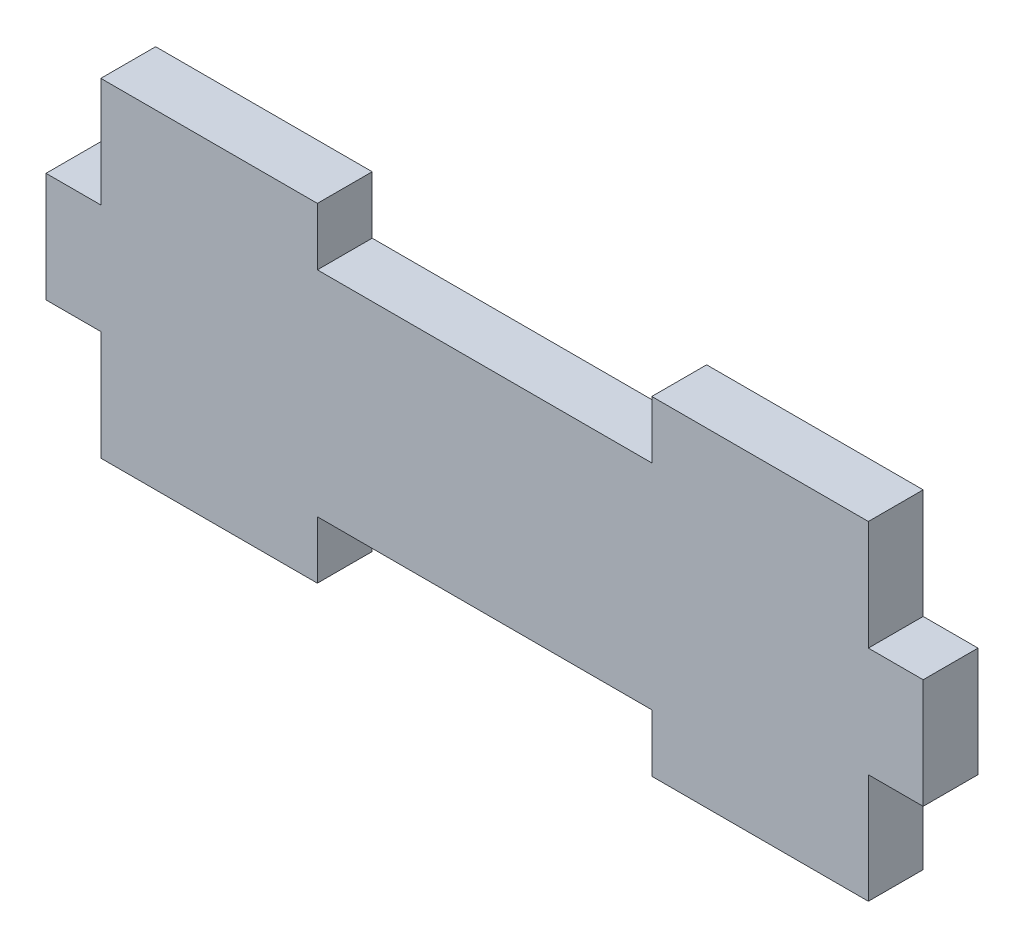
SolidWorks part; units mm, degrees
ref_plane "Front Plane" through (0, 0, 0) normal (0, 0, 1) x (1, 0, 0)
ref_plane "Top Plane" through (0, 0, 0) normal (0, 1, 0) x (1, 0, 0)
ref_plane "Right Plane" through (0, 0, 0) normal (1, 0, 0) x (0, 0, -1)
sketch "Model" plane through (0, 0, 0) normal (0, 0, 1) x (1, 0, 0)
  line L0 (-181.253, -123.7291) -> (-181.253, -133.7291)
  line L1 (-181.253, -133.7291) -> (-186.253, -133.7291)
  line L2 (-161.503, -148.4791) -> (-131.003, -148.4791)
  line L3 (-106.253, -143.7291) -> (-111.253, -143.7291)
  line L4 (-186.253, -143.7291) -> (-181.253, -143.7291)
  line L5 (-181.253, -153.7291) -> (-161.503, -153.7291)
  line L6 (-181.253, -143.7291) -> (-181.253, -153.7291)
  line L7 (-161.503, -123.7291) -> (-181.253, -123.7291)
  line L8 (-186.253, -133.7291) -> (-186.253, -143.7291)
  line L9 (-161.503, -153.7291) -> (-161.503, -148.4791)
  line L10 (-131.003, -148.4791) -> (-131.003, -153.7291)
  line L11 (-111.253, -153.7291) -> (-131.003, -153.7291)
  line L12 (-111.253, -143.7291) -> (-111.253, -153.7291)
  line L13 (-106.253, -133.7291) -> (-106.253, -143.7291)
  line L14 (-111.253, -133.7291) -> (-106.253, -133.7291)
  line L15 (-111.253, -123.7291) -> (-111.253, -133.7291)
  line L16 (-131.003, -123.7291) -> (-111.253, -123.7291)
  line L17 (-131.003, -128.9791) -> (-131.003, -123.7291)
  line L18 (-161.503, -128.9791) -> (-131.003, -128.9791)
  line L19 (-161.503, -123.7291) -> (-161.503, -128.9791)
  line L20 (-154.4137, -142.4791) -> (-138.0923, -142.4791)
  line L21 (-126.8852, -146.7291) -> (-126.8852, -151.7291)
  line L22 (-127.8852, -149.7291) -> (-126.8852, -151.7291)
  line L23 (-125.8852, -149.7291) -> (-126.8852, -151.7291)
  line L24 (-121.1374, -150.5624) -> (-121.1374, -150.2564)
  line L25 (-121.1577, -150.6587) -> (-121.1374, -150.5624)
  line L26 (-116.2735, -151.0431) -> (-116.7144, -151.008)
  line L27 (-123.3653, -147.1199) -> (-123.3852, -147.2159)
  line L28 (-117.3773, -150.6585) -> (-117.317, -150.7473)
  line L29 (-119.3329, -146.7291) -> (-119.9448, -149.2204)
  line L30 (-121.2185, -150.7481) -> (-121.1577, -150.6587)
  line L31 (-121.4621, -150.9058) -> (-121.2185, -150.7481)
  line L32 (-122.6999, -146.7711) -> (-123.0667, -146.8788)
  line L33 (-117.3974, -146.7352) -> (-117.3974, -148.8517)
  line L34 (-117.3974, -148.8517) -> (-117.1788, -148.5973)
  line L35 (-117.3773, -150.6585) -> (-117.3974, -150.5624)
  line L36 (-119.9448, -149.2204) -> (-118.6835, -149.2261)
  line L37 (-122.7061, -151.0088) -> (-122.2613, -151.0431)
  line L38 (-117.3974, -146.7352) -> (-115.2245, -146.7352)
  line L39 (-117.1788, -148.5973) -> (-116.9478, -148.4708)
  line L40 (-116.9478, -148.4708) -> (-116.2735, -148.3709)
  line L41 (-121.1374, -147.2159) -> (-121.1577, -147.1223)
  line L42 (-123.3852, -147.2159) -> (-123.3852, -150.5624)
  line L43 (-123.3056, -150.7512) -> (-123.0667, -150.9058)
  line L44 (-122.2613, -151.0431) -> (-121.8179, -151.0088)
  line L45 (-118.209, -151.0431) -> (-118.6835, -149.2261)
  line L46 (-118.6835, -149.2261) -> (-119.3329, -146.7291)
  line L47 (-116.7144, -151.008) -> (-117.0758, -150.9026)
  line L48 (-123.0667, -150.9058) -> (-122.7061, -151.0088)
  line L49 (-123.3056, -147.0317) -> (-123.3653, -147.1199)
  line L50 (-121.4621, -146.8788) -> (-121.8273, -146.7711)
  line L51 (-121.8273, -146.7711) -> (-122.2613, -146.7352)
  line L52 (-123.0667, -146.8788) -> (-123.3056, -147.0317)
  line L53 (-123.3653, -150.6611) -> (-123.3056, -150.7512)
  line L54 (-117.317, -150.7473) -> (-117.0758, -150.9026)
  line L55 (-121.1374, -147.2159) -> (-121.1374, -147.5219)
  line L56 (-122.2613, -146.7352) -> (-122.6999, -146.7711)
  line L57 (-123.3852, -150.5624) -> (-123.3653, -150.6611)
  line L58 (-121.1577, -147.1223) -> (-121.2185, -147.0349)
  line L59 (-121.8179, -151.0088) -> (-121.4621, -150.9058)
  line L60 (-121.2185, -147.0349) -> (-121.4621, -146.8788)
  line L61 (-115.1697, -150.6585) -> (-115.2299, -150.7473)
  line L62 (-115.2299, -150.7473) -> (-115.4711, -150.9026)
  line L63 (-115.4711, -148.5114) -> (-115.2299, -148.6667)
  line L64 (-115.4711, -150.9026) -> (-115.8325, -151.008)
  line L65 (-115.8325, -148.406) -> (-115.4711, -148.5114)
  line L66 (-116.2735, -148.3709) -> (-115.8325, -148.406)
  line L67 (-119.9448, -149.2204) -> (-120.3943, -151.0431)
  line L68 (-115.2299, -148.6667) -> (-115.1697, -148.7555)
  line L69 (-115.1496, -150.5624) -> (-115.1697, -150.6585)
  line L70 (-115.8325, -151.008) -> (-116.2735, -151.0431)
  line L71 (-115.1697, -148.7555) -> (-115.1496, -148.8517)
  line L72 (-115.1496, -148.8517) -> (-115.1496, -150.5624)
  line L73 (-115.4904, -130.5886) -> (-115.8517, -130.694)
  line L74 (-115.8517, -130.694) -> (-116.2927, -130.7291)
  line L75 (-120.4136, -128.5502) -> (-120.4136, -126.4212)
  line L76 (-121.1566, -127.2078) -> (-121.1566, -126.9019)
  line L77 (-117.3362, -130.4333) -> (-117.3965, -130.3445)
  line L78 (-117.0951, -130.5886) -> (-117.3362, -130.4333)
  line L79 (-120.4136, -130.7291) -> (-120.4136, -128.5502)
  line L80 (-118.5841, -128.5502) -> (-120.4136, -128.5502)
  line L81 (-118.2844, -126.4212) -> (-120.4136, -126.4212)
  line L82 (-117.4166, -130.2483) -> (-117.3965, -130.3445)
  line L83 (-121.1769, -126.8083) -> (-121.1566, -126.9019)
  line L84 (-115.1688, -130.2483) -> (-115.1889, -130.3445)
  line L85 (-115.1889, -130.3445) -> (-115.2492, -130.4333)
  line L86 (-115.2492, -130.4333) -> (-115.4904, -130.5886)
  line L87 (-115.2492, -128.3527) -> (-115.1889, -128.4415)
  line L88 (-115.1889, -128.4415) -> (-115.1688, -128.5377)
  line L89 (-115.1688, -128.5377) -> (-115.1688, -130.2483)
  line L90 (-116.9671, -128.1568) -> (-117.1981, -128.2832)
  line L91 (-116.2927, -128.0569) -> (-115.8517, -128.092)
  line L92 (-115.8517, -128.092) -> (-115.4904, -128.1974)
  line L93 (-115.4904, -128.1974) -> (-115.2492, -128.3527)
  line L94 (-115.2438, -126.4212) -> (-117.4166, -126.4212)
  line L95 (-117.4166, -126.4212) -> (-117.4166, -128.5377)
  line L96 (-117.4166, -128.5377) -> (-117.1981, -128.2832)
  line L97 (-116.2927, -128.0569) -> (-116.9671, -128.1568)
  line L98 (-116.2927, -130.7291) -> (-116.7337, -130.694)
  line L99 (-116.7337, -130.694) -> (-117.0951, -130.5886)
  line L100 (-121.1769, -130.3447) -> (-121.2378, -130.4341)
  line L101 (-123.086, -130.5917) -> (-123.3248, -130.4372)
  line L102 (-123.3845, -130.3471) -> (-123.4044, -130.2483)
  line L103 (-123.4044, -130.2483) -> (-123.4044, -126.9019)
  line L104 (-121.1566, -129.9424) -> (-121.1566, -130.2483)
  line L105 (-121.8372, -130.6948) -> (-122.2805, -130.7291)
  line L106 (-122.2805, -130.7291) -> (-122.7254, -130.6948)
  line L107 (-123.4044, -126.9019) -> (-123.3845, -126.8059)
  line L108 (-123.3845, -126.8059) -> (-123.3248, -126.7177)
  line L109 (-123.3248, -126.7177) -> (-123.086, -126.5647)
  line L110 (-123.086, -126.5647) -> (-122.7192, -126.4571)
  line L111 (-122.2805, -126.4212) -> (-121.8466, -126.4571)
  line L112 (-121.1566, -130.2483) -> (-121.1769, -130.3447)
  line L113 (-122.7254, -130.6948) -> (-123.086, -130.5917)
  line L114 (-123.3248, -130.4372) -> (-123.3845, -130.3471)
  line L115 (-122.7192, -126.4571) -> (-122.2805, -126.4212)
  line L116 (-121.2378, -130.4341) -> (-121.4813, -130.5917)
  line L117 (-121.4813, -130.5917) -> (-121.8372, -130.6948)
  line L118 (-121.8466, -126.4571) -> (-121.4813, -126.5647)
  line L119 (-121.4813, -126.5647) -> (-121.2378, -126.7208)
  line L120 (-121.2378, -126.7208) -> (-121.1769, -126.8083)
  line L121 (-126.8852, -130.7291) -> (-126.8852, -125.7291)
  line L122 (-125.8852, -127.7291) -> (-126.8852, -125.7291)
  line L123 (-127.8852, -127.7291) -> (-126.8852, -125.7291)
  line L124 (-174.5052, -140.0964) -> (-174.5052, -140.4023)
  line L125 (-174.5052, -140.4023) -> (-174.5255, -140.4987)
  line L126 (-174.5255, -140.4987) -> (-174.5863, -140.588)
  line L127 (-174.5863, -140.588) -> (-174.8299, -140.7457)
  line L128 (-174.8299, -140.7457) -> (-175.1857, -140.8487)
  line L129 (-175.1857, -140.8487) -> (-175.6291, -140.8831)
  line L130 (-175.6291, -140.8831) -> (-176.074, -140.8487)
  line L131 (-176.074, -140.8487) -> (-176.4345, -140.7457)
  line L132 (-176.4345, -140.7457) -> (-176.6734, -140.5912)
  line L133 (-176.6734, -140.5912) -> (-176.7331, -140.501)
  line L134 (-176.7331, -140.501) -> (-176.753, -140.4023)
  line L135 (-176.753, -140.4023) -> (-176.753, -137.0559)
  line L136 (-176.753, -137.0559) -> (-176.7331, -136.9599)
  line L137 (-176.7331, -136.9599) -> (-176.6734, -136.8717)
  line L138 (-176.6734, -136.8717) -> (-176.4345, -136.7187)
  line L139 (-176.4345, -136.7187) -> (-176.0677, -136.611)
  line L140 (-176.0677, -136.611) -> (-175.6291, -136.5751)
  line L141 (-175.6291, -136.5751) -> (-175.1951, -136.611)
  line L142 (-175.1951, -136.611) -> (-174.8299, -136.7187)
  line L143 (-174.8299, -136.7187) -> (-174.5863, -136.8748)
  line L144 (-174.5863, -136.8748) -> (-174.5255, -136.9622)
  line L145 (-174.5255, -136.9622) -> (-174.5052, -137.0559)
  line L146 (-174.5052, -137.0559) -> (-174.5052, -137.3618)
  line L147 (-174.5052, -137.3618) -> (-174.5052, -137.0559)
  line L148 (-174.5052, -137.0559) -> (-174.5255, -136.9622)
  line L149 (-174.5255, -136.9622) -> (-174.5863, -136.8748)
  line L150 (-174.5863, -136.8748) -> (-174.8299, -136.7187)
  line L151 (-174.8299, -136.7187) -> (-175.1951, -136.611)
  line L152 (-175.1951, -136.611) -> (-175.6291, -136.5751)
  line L153 (-175.6291, -136.5751) -> (-176.0677, -136.611)
  line L154 (-176.0677, -136.611) -> (-176.4345, -136.7187)
  line L155 (-176.4345, -136.7187) -> (-176.6734, -136.8717)
  line L156 (-176.6734, -136.8717) -> (-176.7331, -136.9599)
  line L157 (-176.7331, -136.9599) -> (-176.753, -137.0559)
  line L158 (-176.753, -137.0559) -> (-176.753, -140.4023)
  line L159 (-176.753, -140.4023) -> (-176.7331, -140.501)
  line L160 (-176.7331, -140.501) -> (-176.6734, -140.5912)
  line L161 (-176.6734, -140.5912) -> (-176.4345, -140.7457)
  line L162 (-176.4345, -140.7457) -> (-176.074, -140.8487)
  line L163 (-176.074, -140.8487) -> (-175.6291, -140.8831)
  line L164 (-175.6291, -140.8831) -> (-175.1857, -140.8487)
  line L165 (-175.1857, -140.8487) -> (-174.8299, -140.7457)
  line L166 (-174.8299, -140.7457) -> (-174.5863, -140.588)
  line L167 (-174.5863, -140.588) -> (-174.5255, -140.4987)
  line L168 (-174.5255, -140.4987) -> (-174.5052, -140.4023)
  line L169 (-174.5052, -140.4023) -> (-174.5052, -140.0964)
  line L170 (-173.7621, -140.883) -> (-173.7621, -136.5751)
  line L171 (-173.7621, -136.5751) -> (-171.6329, -136.5751)
  line L172 (-171.6329, -136.5751) -> (-173.7621, -136.5751)
  line L173 (-173.7621, -136.5751) -> (-173.7621, -138.6666)
  line L174 (-173.7621, -138.6666) -> (-171.9327, -138.6666)
  line L175 (-171.9327, -138.6666) -> (-173.7621, -138.6666)
  line L176 (-173.7621, -138.6666) -> (-173.7621, -140.883)
  line L177 (-173.7621, -140.883) -> (-171.6329, -140.883)
  line L178 (-171.6329, -140.883) -> (-173.7621, -140.883)
  line L179 (-169.6413, -140.883) -> (-170.0823, -140.8479)
  line L180 (-170.0823, -140.8479) -> (-170.4436, -140.7426)
  line L181 (-170.4436, -140.7426) -> (-170.6848, -140.5873)
  line L182 (-170.6848, -140.5873) -> (-170.7451, -140.4985)
  line L183 (-170.7451, -140.4985) -> (-170.7652, -140.4023)
  line L184 (-170.7652, -140.4023) -> (-170.7451, -140.4985)
  line L185 (-170.7451, -140.4985) -> (-170.6848, -140.5873)
  line L186 (-170.6848, -140.5873) -> (-170.4436, -140.7426)
  line L187 (-168.8389, -140.7426) -> (-168.5977, -140.5873)
  line L188 (-168.5977, -140.5873) -> (-168.5375, -140.4985)
  line L189 (-168.5375, -140.4985) -> (-168.5174, -140.4023)
  line L190 (-168.5174, -140.4023) -> (-168.5174, -138.6916)
  line L191 (-168.5174, -138.6916) -> (-168.5375, -138.5954)
  line L192 (-168.5375, -138.5954) -> (-168.5977, -138.5066)
  line L193 (-168.5977, -138.5066) -> (-168.8389, -138.3513)
  line L194 (-168.8389, -138.3513) -> (-169.2003, -138.246)
  line L195 (-169.2003, -138.246) -> (-169.6413, -138.2108)
  line L196 (-169.6413, -138.2108) -> (-170.3156, -138.3108)
  line L197 (-170.3156, -138.3108) -> (-170.5466, -138.4372)
  line L198 (-170.5466, -138.4372) -> (-170.7652, -138.6916)
  line L199 (-170.7652, -138.6916) -> (-170.7652, -136.5751)
  line L200 (-170.7652, -136.5751) -> (-168.5923, -136.5751)
  line L201 (-168.5923, -136.5751) -> (-170.7652, -136.5751)
  line L202 (-170.7652, -136.5751) -> (-170.7652, -138.6916)
  line L203 (-170.7652, -138.6916) -> (-170.5466, -138.4372)
  line L204 (-170.5466, -138.4372) -> (-170.3156, -138.3108)
  line L205 (-170.3156, -138.3108) -> (-169.6413, -138.2108)
  line L206 (-169.6413, -138.2108) -> (-169.2003, -138.246)
  line L207 (-169.2003, -138.246) -> (-168.8389, -138.3513)
  line L208 (-168.8389, -138.3513) -> (-168.5977, -138.5066)
  line L209 (-168.5977, -138.5066) -> (-168.5375, -138.5954)
  line L210 (-168.5375, -138.5954) -> (-168.5174, -138.6916)
  line L211 (-168.5174, -138.6916) -> (-168.5174, -140.4023)
  line L212 (-168.5174, -140.4023) -> (-168.5375, -140.4985)
  line L213 (-168.5375, -140.4985) -> (-168.5977, -140.5873)
  line L214 (-168.5977, -140.5873) -> (-168.8389, -140.7426)
  line L215 (-168.8389, -140.7426) -> (-169.2003, -140.8479)
  line L216 (-169.2003, -140.8479) -> (-169.6413, -140.883)
  line L217 (-179.253, -138.7291) -> (-184.253, -138.7291)
  line L218 (-182.253, -137.7291) -> (-184.253, -138.7291)
  line L219 (-182.253, -139.7291) -> (-184.253, -138.7291)
  line L220 (-149.918, -139.9057) -> (-149.918, -140.5176)
  line L221 (-149.918, -140.5176) -> (-149.9586, -140.7103)
  line L222 (-149.9586, -140.7103) -> (-150.0804, -140.8891)
  line L223 (-150.0804, -140.8891) -> (-150.5674, -141.2044)
  line L224 (-150.5674, -141.2044) -> (-151.2792, -141.4104)
  line L225 (-151.2792, -141.4104) -> (-152.1658, -141.4791)
  line L226 (-152.1658, -141.4791) -> (-153.0556, -141.4104)
  line L227 (-153.0556, -141.4104) -> (-153.7767, -141.2044)
  line L228 (-153.7767, -141.2044) -> (-154.2544, -140.8953)
  line L229 (-154.2544, -140.8953) -> (-154.3738, -140.715)
  line L230 (-154.3738, -140.715) -> (-154.4137, -140.5176)
  line L231 (-154.4137, -140.5176) -> (-154.4137, -133.8247)
  line L232 (-154.4137, -133.8247) -> (-154.3738, -133.6328)
  line L233 (-154.3738, -133.6328) -> (-154.2544, -133.4564)
  line L234 (-154.2544, -133.4564) -> (-153.7767, -133.1504)
  line L235 (-153.7767, -133.1504) -> (-153.0431, -132.935)
  line L236 (-153.0431, -132.935) -> (-152.1658, -132.8632)
  line L237 (-152.1658, -132.8632) -> (-151.298, -132.935)
  line L238 (-151.298, -132.935) -> (-150.5674, -133.1504)
  line L239 (-150.5674, -133.1504) -> (-150.0804, -133.4626)
  line L240 (-150.0804, -133.4626) -> (-149.9586, -133.6374)
  line L241 (-149.9586, -133.6374) -> (-149.918, -133.8247)
  line L242 (-149.918, -133.8247) -> (-149.918, -134.4366)
  line L243 (-149.918, -134.4366) -> (-149.918, -133.8247)
  line L244 (-149.918, -133.8247) -> (-149.9586, -133.6374)
  line L245 (-149.9586, -133.6374) -> (-150.0804, -133.4626)
  line L246 (-150.0804, -133.4626) -> (-150.5674, -133.1504)
  line L247 (-150.5674, -133.1504) -> (-151.298, -132.935)
  line L248 (-151.298, -132.935) -> (-152.1658, -132.8632)
  line L249 (-152.1658, -132.8632) -> (-153.0431, -132.935)
  line L250 (-153.0431, -132.935) -> (-153.7767, -133.1504)
  line L251 (-153.7767, -133.1504) -> (-154.2544, -133.4564)
  line L252 (-154.2544, -133.4564) -> (-154.3738, -133.6328)
  line L253 (-154.3738, -133.6328) -> (-154.4137, -133.8247)
  line L254 (-154.4137, -133.8247) -> (-154.4137, -140.5176)
  line L255 (-154.4137, -140.5176) -> (-154.3738, -140.715)
  line L256 (-154.3738, -140.715) -> (-154.2544, -140.8953)
  line L257 (-154.2544, -140.8953) -> (-153.7767, -141.2044)
  line L258 (-153.7767, -141.2044) -> (-153.0556, -141.4104)
  line L259 (-153.0556, -141.4104) -> (-152.1658, -141.4791)
  line L260 (-152.1658, -141.4791) -> (-151.2792, -141.4104)
  line L261 (-151.2792, -141.4104) -> (-150.5674, -141.2044)
  line L262 (-150.5674, -141.2044) -> (-150.0804, -140.8891)
  line L263 (-150.0804, -140.8891) -> (-149.9586, -140.7103)
  line L264 (-149.9586, -140.7103) -> (-149.918, -140.5176)
  line L265 (-149.918, -140.5176) -> (-149.918, -139.9057)
  line L266 (-148.4319, -141.4791) -> (-148.4319, -132.8632)
  line L267 (-148.4319, -132.8632) -> (-146.3964, -132.8632)
  line L268 (-146.3964, -132.8632) -> (-145.5285, -132.935)
  line L269 (-145.5285, -132.935) -> (-144.798, -133.1504)
  line L270 (-144.798, -133.1504) -> (-144.311, -133.4626)
  line L271 (-144.311, -133.4626) -> (-144.1892, -133.6374)
  line L272 (-144.1892, -133.6374) -> (-144.1486, -133.8247)
  line L273 (-144.1486, -133.8247) -> (-144.1486, -140.5176)
  line L274 (-144.1486, -140.5176) -> (-144.1892, -140.7103)
  line L275 (-144.1892, -140.7103) -> (-144.311, -140.8891)
  line L276 (-144.311, -140.8891) -> (-144.798, -141.2044)
  line L277 (-144.798, -141.2044) -> (-145.5098, -141.4104)
  line L278 (-145.5098, -141.4104) -> (-146.3964, -141.4791)
  line L279 (-146.3964, -141.4791) -> (-148.4319, -141.4791)
  line L280 (-148.4319, -132.8632) -> (-148.4319, -141.4791)
  line L281 (-148.4319, -141.4791) -> (-146.3964, -141.4791)
  line L282 (-146.3964, -141.4791) -> (-145.5098, -141.4104)
  line L283 (-145.5098, -141.4104) -> (-144.798, -141.2044)
  line L284 (-144.798, -141.2044) -> (-144.311, -140.8891)
  line L285 (-144.311, -140.8891) -> (-144.1892, -140.7103)
  line L286 (-144.1892, -140.7103) -> (-144.1486, -140.5176)
  line L287 (-144.1486, -140.5176) -> (-144.1486, -133.8247)
  line L288 (-144.1486, -133.8247) -> (-144.1892, -133.6374)
  line L289 (-144.1892, -133.6374) -> (-144.311, -133.4626)
  line L290 (-144.311, -133.4626) -> (-144.798, -133.1504)
  line L291 (-144.798, -133.1504) -> (-145.5285, -132.935)
  line L292 (-145.5285, -132.935) -> (-146.3964, -132.8632)
  line L293 (-146.3964, -132.8632) -> (-148.4319, -132.8632)
  line L294 (-140.1902, -141.4791) -> (-141.0722, -141.4088)
  line L295 (-141.0722, -141.4088) -> (-141.7949, -141.1981)
  line L296 (-141.7949, -141.1981) -> (-142.2773, -140.8875)
  line L297 (-142.2773, -140.8875) -> (-142.3979, -140.71)
  line L298 (-142.3979, -140.71) -> (-142.438, -140.5176)
  line L299 (-142.438, -140.5176) -> (-142.3979, -140.71)
  line L300 (-142.3979, -140.71) -> (-142.2773, -140.8875)
  line L301 (-142.2773, -140.8875) -> (-141.7949, -141.1981)
  line L302 (-138.5855, -141.1981) -> (-138.1032, -140.8875)
  line L303 (-138.1032, -140.8875) -> (-137.9826, -140.71)
  line L304 (-137.9826, -140.71) -> (-137.9424, -140.5176)
  line L305 (-137.9424, -140.5176) -> (-137.9424, -137.0963)
  line L306 (-137.9424, -137.0963) -> (-137.9826, -136.9039)
  line L307 (-137.9826, -136.9039) -> (-138.1032, -136.7263)
  line L308 (-138.1032, -136.7263) -> (-138.5855, -136.4156)
  line L309 (-138.5855, -136.4156) -> (-139.3083, -136.2049)
  line L310 (-139.3083, -136.2049) -> (-140.1902, -136.1347)
  line L311 (-140.1902, -136.1347) -> (-141.5389, -136.3345)
  line L312 (-141.5389, -136.3345) -> (-142.001, -136.5874)
  line L313 (-142.001, -136.5874) -> (-142.438, -137.0963)
  line L314 (-142.438, -137.0963) -> (-142.438, -132.8632)
  line L315 (-142.438, -132.8632) -> (-138.0923, -132.8632)
  line L316 (-138.0923, -132.8632) -> (-142.438, -132.8632)
  line L317 (-142.438, -132.8632) -> (-142.438, -137.0963)
  line L318 (-142.438, -137.0963) -> (-142.001, -136.5874)
  line L319 (-142.001, -136.5874) -> (-141.5389, -136.3345)
  line L320 (-141.5389, -136.3345) -> (-140.1902, -136.1347)
  line L321 (-140.1902, -136.1347) -> (-139.3083, -136.2049)
  line L322 (-139.3083, -136.2049) -> (-138.5855, -136.4156)
  line L323 (-138.5855, -136.4156) -> (-138.1032, -136.7263)
  line L324 (-138.1032, -136.7263) -> (-137.9826, -136.9039)
  line L325 (-137.9826, -136.9039) -> (-137.9424, -137.0963)
  line L326 (-137.9424, -137.0963) -> (-137.9424, -140.5176)
  line L327 (-137.9424, -140.5176) -> (-137.9826, -140.71)
  line L328 (-137.9826, -140.71) -> (-138.1032, -140.8875)
  line L329 (-138.1032, -140.8875) -> (-138.5855, -141.1981)
  line L330 (-138.5855, -141.1981) -> (-139.3083, -141.4088)
  line L331 (-139.3083, -141.4088) -> (-140.1902, -141.4791)
  line L332 (-152.9169, -143.4791) -> (-153.457, -143.4791)
  line L333 (-153.457, -143.4791) -> (-152.3861, -143.4791)
  line L334 (-152.3861, -143.4791) -> (-152.9169, -143.4791)
  line L335 (-152.9169, -143.4791) -> (-152.9169, -145.6331)
  line L336 (-152.9169, -145.6331) -> (-152.9169, -143.4791)
  line L337 (-151.9585, -145.6331) -> (-151.9585, -143.4791)
  line L338 (-151.9585, -143.4791) -> (-151.9585, -144.5406)
  line L339 (-151.9585, -144.5406) -> (-150.8408, -144.5406)
  line L340 (-150.8408, -144.5406) -> (-150.8408, -143.4791)
  line L341 (-150.8408, -143.4791) -> (-150.8408, -145.6331)
  line L342 (-150.8408, -145.6331) -> (-150.8408, -144.5404)
  line L343 (-150.8408, -144.5404) -> (-151.9585, -144.5404)
  line L344 (-151.9585, -144.5404) -> (-151.9585, -145.6331)
  line L345 (-150.46, -143.476) -> (-150.46, -145.6331)
  line L346 (-149.96, -145.2397) -> (-149.96, -145.3927)
  line L347 (-149.96, -145.3927) -> (-149.95, -145.4408)
  line L348 (-149.95, -145.4408) -> (-149.9198, -145.4852)
  line L349 (-149.9198, -145.4852) -> (-149.7992, -145.5628)
  line L350 (-149.7992, -145.5628) -> (-149.6185, -145.6155)
  line L351 (-149.6185, -145.6155) -> (-149.3981, -145.6331)
  line L352 (-149.3981, -145.6331) -> (-149.1776, -145.6155)
  line L353 (-149.1776, -145.6155) -> (-148.9969, -145.5628)
  line L354 (-148.9969, -145.5628) -> (-148.8763, -145.4852)
  line L355 (-148.8763, -145.4852) -> (-148.8462, -145.4408)
  line L356 (-148.8462, -145.4408) -> (-148.8361, -145.3927)
  line L357 (-148.8361, -145.3927) -> (-148.8299, -144.7559)
  line L358 (-148.8299, -144.7559) -> (-148.8581, -144.63)
  line L359 (-148.8581, -144.63) -> (-148.9395, -144.5397)
  line L360 (-148.9395, -144.5397) -> (-149.0743, -144.4848)
  line L361 (-149.0743, -144.4848) -> (-149.2623, -144.4655)
  line L362 (-149.2623, -144.4655) -> (-149.6029, -144.457)
  line L363 (-149.6029, -144.457) -> (-149.7665, -144.4375)
  line L364 (-149.7665, -144.4375) -> (-149.9116, -144.3555)
  line L365 (-149.9116, -144.3555) -> (-149.9479, -144.3069)
  line L366 (-149.9479, -144.3069) -> (-149.96, -144.2533)
  line L367 (-149.96, -144.2533) -> (-149.96, -143.7195)
  line L368 (-149.96, -143.7195) -> (-149.95, -143.6714)
  line L369 (-149.95, -143.6714) -> (-149.9198, -143.627)
  line L370 (-149.9198, -143.627) -> (-149.7992, -143.5493)
  line L371 (-149.7992, -143.5493) -> (-149.6185, -143.4966)
  line L372 (-149.6185, -143.4966) -> (-149.3981, -143.4791)
  line L373 (-149.3981, -143.4791) -> (-149.1776, -143.4966)
  line L374 (-149.1776, -143.4966) -> (-148.9969, -143.5493)
  line L375 (-148.9969, -143.5493) -> (-148.8763, -143.627)
  line L376 (-148.8763, -143.627) -> (-148.8462, -143.6714)
  line L377 (-148.8462, -143.6714) -> (-148.8361, -143.7195)
  line L378 (-148.8361, -143.7195) -> (-148.8361, -143.8724)
  line L379 (-148.8361, -143.8724) -> (-148.8361, -143.7195)
  line L380 (-148.8361, -143.7195) -> (-148.8462, -143.6714)
  line L381 (-148.8462, -143.6714) -> (-148.8763, -143.627)
  line L382 (-148.8763, -143.627) -> (-148.9969, -143.5493)
  line L383 (-148.9969, -143.5493) -> (-149.1776, -143.4966)
  line L384 (-149.1776, -143.4966) -> (-149.3981, -143.4791)
  line L385 (-149.3981, -143.4791) -> (-149.6185, -143.4966)
  line L386 (-149.6185, -143.4966) -> (-149.7992, -143.5493)
  line L387 (-149.7992, -143.5493) -> (-149.9198, -143.627)
  line L388 (-149.9198, -143.627) -> (-149.95, -143.6714)
  line L389 (-149.95, -143.6714) -> (-149.96, -143.7195)
  line L390 (-149.96, -143.7195) -> (-149.96, -144.2533)
  line L391 (-149.96, -144.2533) -> (-149.9479, -144.3069)
  line L392 (-149.9479, -144.3069) -> (-149.9116, -144.3555)
  line L393 (-149.9116, -144.3555) -> (-149.7665, -144.4375)
  line L394 (-149.7665, -144.4375) -> (-149.6029, -144.457)
  line L395 (-149.6029, -144.457) -> (-149.2623, -144.4655)
  line L396 (-149.2623, -144.4655) -> (-149.0743, -144.4848)
  line L397 (-149.0743, -144.4848) -> (-148.9395, -144.5397)
  line L398 (-148.9395, -144.5397) -> (-148.8581, -144.63)
  line L399 (-148.8581, -144.63) -> (-148.8299, -144.7559)
  line L400 (-148.8299, -144.7559) -> (-148.8361, -145.3927)
  line L401 (-148.8361, -145.3927) -> (-148.8462, -145.4408)
  line L402 (-148.8462, -145.4408) -> (-148.8763, -145.4852)
  line L403 (-148.8763, -145.4852) -> (-148.9969, -145.5628)
  line L404 (-148.9969, -145.5628) -> (-149.1776, -145.6155)
  line L405 (-149.1776, -145.6155) -> (-149.3981, -145.6331)
  line L406 (-149.3981, -145.6331) -> (-149.6185, -145.6155)
  line L407 (-149.6185, -145.6155) -> (-149.7992, -145.5628)
  line L408 (-149.7992, -145.5628) -> (-149.9198, -145.4852)
  line L409 (-149.9198, -145.4852) -> (-149.95, -145.4408)
  line L410 (-149.95, -145.4408) -> (-149.96, -145.3927)
  line L411 (-149.96, -145.3927) -> (-149.96, -145.2397)
  line L412 (-147.2161, -145.2397) -> (-147.2161, -145.3927)
  line L413 (-147.2161, -145.3927) -> (-147.2061, -145.4408)
  line L414 (-147.2061, -145.4408) -> (-147.1759, -145.4852)
  line L415 (-147.1759, -145.4852) -> (-147.0553, -145.5628)
  line L416 (-147.0553, -145.5628) -> (-146.8746, -145.6155)
  line L417 (-146.8746, -145.6155) -> (-146.6542, -145.6331)
  line L418 (-146.6542, -145.6331) -> (-146.4337, -145.6155)
  line L419 (-146.4337, -145.6155) -> (-146.253, -145.5628)
  line L420 (-146.253, -145.5628) -> (-146.1324, -145.4852)
  line L421 (-146.1324, -145.4852) -> (-146.1022, -145.4408)
  line L422 (-146.1022, -145.4408) -> (-146.0922, -145.3927)
  line L423 (-146.0922, -145.3927) -> (-146.086, -144.7559)
  line L424 (-146.086, -144.7559) -> (-146.1142, -144.63)
  line L425 (-146.1142, -144.63) -> (-146.1956, -144.5397)
  line L426 (-146.1956, -144.5397) -> (-146.3303, -144.4848)
  line L427 (-146.3303, -144.4848) -> (-146.5184, -144.4655)
  line L428 (-146.5184, -144.4655) -> (-146.859, -144.457)
  line L429 (-146.859, -144.457) -> (-147.0226, -144.4375)
  line L430 (-147.0226, -144.4375) -> (-147.1677, -144.3555)
  line L431 (-147.1677, -144.3555) -> (-147.204, -144.3069)
  line L432 (-147.204, -144.3069) -> (-147.2161, -144.2533)
  line L433 (-147.2161, -144.2533) -> (-147.2161, -143.7195)
  line L434 (-147.2161, -143.7195) -> (-147.2061, -143.6714)
  line L435 (-147.2061, -143.6714) -> (-147.1759, -143.627)
  line L436 (-147.1759, -143.627) -> (-147.0553, -143.5493)
  line L437 (-147.0553, -143.5493) -> (-146.8746, -143.4966)
  line L438 (-146.8746, -143.4966) -> (-146.6542, -143.4791)
  line L439 (-146.6542, -143.4791) -> (-146.4337, -143.4966)
  line L440 (-146.4337, -143.4966) -> (-146.253, -143.5493)
  line L441 (-146.253, -143.5493) -> (-146.1324, -143.627)
  line L442 (-146.1324, -143.627) -> (-146.1022, -143.6714)
  line L443 (-146.1022, -143.6714) -> (-146.0922, -143.7195)
  line L444 (-146.0922, -143.7195) -> (-146.0922, -143.8724)
  line L445 (-146.0922, -143.8724) -> (-146.0922, -143.7195)
  line L446 (-146.0922, -143.7195) -> (-146.1022, -143.6714)
  line L447 (-146.1022, -143.6714) -> (-146.1324, -143.627)
  line L448 (-146.1324, -143.627) -> (-146.253, -143.5493)
  line L449 (-146.253, -143.5493) -> (-146.4337, -143.4966)
  line L450 (-146.4337, -143.4966) -> (-146.6542, -143.4791)
  line L451 (-146.6542, -143.4791) -> (-146.8746, -143.4966)
  line L452 (-146.8746, -143.4966) -> (-147.0553, -143.5493)
  line L453 (-147.0553, -143.5493) -> (-147.1759, -143.627)
  line L454 (-147.1759, -143.627) -> (-147.2061, -143.6714)
  line L455 (-147.2061, -143.6714) -> (-147.2161, -143.7195)
  line L456 (-147.2161, -143.7195) -> (-147.2161, -144.2533)
  line L457 (-147.2161, -144.2533) -> (-147.204, -144.3069)
  line L458 (-147.204, -144.3069) -> (-147.1677, -144.3555)
  line L459 (-147.1677, -144.3555) -> (-147.0226, -144.4375)
  line L460 (-147.0226, -144.4375) -> (-146.859, -144.457)
  line L461 (-146.859, -144.457) -> (-146.5184, -144.4655)
  line L462 (-146.5184, -144.4655) -> (-146.3303, -144.4848)
  line L463 (-146.3303, -144.4848) -> (-146.1956, -144.5397)
  line L464 (-146.1956, -144.5397) -> (-146.1142, -144.63)
  line L465 (-146.1142, -144.63) -> (-146.086, -144.7559)
  line L466 (-146.086, -144.7559) -> (-146.0922, -145.3927)
  line L467 (-146.0922, -145.3927) -> (-146.1022, -145.4408)
  line L468 (-146.1022, -145.4408) -> (-146.1324, -145.4852)
  line L469 (-146.1324, -145.4852) -> (-146.253, -145.5628)
  line L470 (-146.253, -145.5628) -> (-146.4337, -145.6155)
  line L471 (-146.4337, -145.6155) -> (-146.6542, -145.6331)
  line L472 (-146.6542, -145.6331) -> (-146.8746, -145.6155)
  line L473 (-146.8746, -145.6155) -> (-147.0553, -145.5628)
  line L474 (-147.0553, -145.5628) -> (-147.1759, -145.4852)
  line L475 (-147.1759, -145.4852) -> (-147.2061, -145.4408)
  line L476 (-147.2061, -145.4408) -> (-147.2161, -145.3927)
  line L477 (-147.2161, -145.3927) -> (-147.2161, -145.2397)
  line L478 (-145.7207, -143.476) -> (-145.7207, -145.6331)
  line L479 (-145.2207, -145.6331) -> (-145.2207, -143.4791)
  line L480 (-145.2207, -143.4791) -> (-144.7118, -143.4791)
  line L481 (-144.7118, -143.4791) -> (-144.4948, -143.497)
  line L482 (-144.4948, -143.497) -> (-144.3122, -143.5509)
  line L483 (-144.3122, -143.5509) -> (-144.1904, -143.6289)
  line L484 (-144.1904, -143.6289) -> (-144.16, -143.6726)
  line L485 (-144.16, -143.6726) -> (-144.1498, -143.7195)
  line L486 (-144.1498, -143.7195) -> (-144.1498, -145.3927)
  line L487 (-144.1498, -145.3927) -> (-144.16, -145.4409)
  line L488 (-144.16, -145.4409) -> (-144.1904, -145.4855)
  line L489 (-144.1904, -145.4855) -> (-144.3122, -145.5644)
  line L490 (-144.3122, -145.5644) -> (-144.4901, -145.6159)
  line L491 (-144.4901, -145.6159) -> (-144.7118, -145.6331)
  line L492 (-144.7118, -145.6331) -> (-145.2207, -145.6331)
  line L493 (-145.2207, -143.4791) -> (-145.2207, -145.6331)
  line L494 (-145.2207, -145.6331) -> (-144.7118, -145.6331)
  line L495 (-144.7118, -145.6331) -> (-144.4901, -145.6159)
  line L496 (-144.4901, -145.6159) -> (-144.3122, -145.5644)
  line L497 (-144.3122, -145.5644) -> (-144.1904, -145.4855)
  line L498 (-144.1904, -145.4855) -> (-144.16, -145.4409)
  line L499 (-144.16, -145.4409) -> (-144.1498, -145.3927)
  line L500 (-144.1498, -145.3927) -> (-144.1498, -143.7195)
  line L501 (-144.1498, -143.7195) -> (-144.16, -143.6726)
  line L502 (-144.16, -143.6726) -> (-144.1904, -143.6289)
  line L503 (-144.1904, -143.6289) -> (-144.3122, -143.5509)
  line L504 (-144.3122, -143.5509) -> (-144.4948, -143.497)
  line L505 (-144.4948, -143.497) -> (-144.7118, -143.4791)
  line L506 (-144.7118, -143.4791) -> (-145.2207, -143.4791)
  line L507 (-143.7222, -145.6331) -> (-143.7222, -143.4791)
  line L508 (-143.7222, -143.4791) -> (-142.6576, -143.4791)
  line L509 (-142.6576, -143.4791) -> (-143.7222, -143.4791)
  line L510 (-143.7222, -143.4791) -> (-143.7222, -144.5248)
  line L511 (-143.7222, -144.5248) -> (-142.8075, -144.5248)
  line L512 (-142.8075, -144.5248) -> (-143.7222, -144.5248)
  line L513 (-143.7222, -144.5248) -> (-143.7222, -145.6331)
  line L514 (-143.7222, -145.6331) -> (-142.6576, -145.6331)
  line L515 (-142.6576, -145.6331) -> (-143.7222, -145.6331)
  line L516 (-140.9753, -143.476) -> (-140.9753, -145.6331)
  line L517 (-140.4753, -145.6331) -> (-140.4753, -143.4791)
  line L518 (-140.4753, -143.4791) -> (-139.3951, -145.6331)
  line L519 (-139.3951, -145.6331) -> (-139.3951, -143.4791)
  line L520 (-139.3951, -143.4791) -> (-139.3951, -145.6331)
  line L521 (-139.3951, -145.6331) -> (-140.4753, -143.4791)
  line L522 (-140.4753, -143.4791) -> (-140.4753, -145.6331)
  line L523 (-121.7408, -140.0964) -> (-121.7408, -140.4023)
  line L524 (-121.7408, -140.4023) -> (-121.7611, -140.4987)
  line L525 (-121.7611, -140.4987) -> (-121.822, -140.588)
  line L526 (-121.822, -140.588) -> (-122.0655, -140.7457)
  line L527 (-122.0655, -140.7457) -> (-122.4214, -140.8487)
  line L528 (-122.4214, -140.8487) -> (-122.8647, -140.8831)
  line L529 (-122.8647, -140.8831) -> (-123.3096, -140.8487)
  line L530 (-123.3096, -140.8487) -> (-123.6701, -140.7457)
  line L531 (-123.6701, -140.7457) -> (-123.909, -140.5912)
  line L532 (-123.909, -140.5912) -> (-123.9687, -140.501)
  line L533 (-123.9687, -140.501) -> (-123.9886, -140.4023)
  line L534 (-123.9886, -140.4023) -> (-123.9886, -137.0559)
  line L535 (-123.9886, -137.0559) -> (-123.9687, -136.9599)
  line L536 (-123.9687, -136.9599) -> (-123.909, -136.8717)
  line L537 (-123.909, -136.8717) -> (-123.6701, -136.7187)
  line L538 (-123.6701, -136.7187) -> (-123.3033, -136.611)
  line L539 (-123.3033, -136.611) -> (-122.8647, -136.5751)
  line L540 (-122.8647, -136.5751) -> (-122.4307, -136.611)
  line L541 (-122.4307, -136.611) -> (-122.0655, -136.7187)
  line L542 (-122.0655, -136.7187) -> (-121.822, -136.8748)
  line L543 (-121.822, -136.8748) -> (-121.7611, -136.9622)
  line L544 (-121.7611, -136.9622) -> (-121.7408, -137.0559)
  line L545 (-121.7408, -137.0559) -> (-121.7408, -137.3618)
  line L546 (-121.7408, -137.3618) -> (-121.7408, -137.0559)
  line L547 (-121.7408, -137.0559) -> (-121.7611, -136.9622)
  line L548 (-121.7611, -136.9622) -> (-121.822, -136.8748)
  line L549 (-121.822, -136.8748) -> (-122.0655, -136.7187)
  line L550 (-122.0655, -136.7187) -> (-122.4307, -136.611)
  line L551 (-122.4307, -136.611) -> (-122.8647, -136.5751)
  line L552 (-122.8647, -136.5751) -> (-123.3033, -136.611)
  line L553 (-123.3033, -136.611) -> (-123.6701, -136.7187)
  line L554 (-123.6701, -136.7187) -> (-123.909, -136.8717)
  line L555 (-123.909, -136.8717) -> (-123.9687, -136.9599)
  line L556 (-123.9687, -136.9599) -> (-123.9886, -137.0559)
  line L557 (-123.9886, -137.0559) -> (-123.9886, -140.4023)
  line L558 (-123.9886, -140.4023) -> (-123.9687, -140.501)
  line L559 (-123.9687, -140.501) -> (-123.909, -140.5912)
  line L560 (-123.909, -140.5912) -> (-123.6701, -140.7457)
  line L561 (-123.6701, -140.7457) -> (-123.3096, -140.8487)
  line L562 (-123.3096, -140.8487) -> (-122.8647, -140.8831)
  line L563 (-122.8647, -140.8831) -> (-122.4214, -140.8487)
  line L564 (-122.4214, -140.8487) -> (-122.0655, -140.7457)
  line L565 (-122.0655, -140.7457) -> (-121.822, -140.588)
  line L566 (-121.822, -140.588) -> (-121.7611, -140.4987)
  line L567 (-121.7611, -140.4987) -> (-121.7408, -140.4023)
  line L568 (-121.7408, -140.4023) -> (-121.7408, -140.0964)
  line L569 (-120.9977, -140.8831) -> (-120.9977, -136.5751)
  line L570 (-120.9977, -136.5751) -> (-118.8685, -136.5751)
  line L571 (-118.8685, -136.5751) -> (-120.9977, -136.5751)
  line L572 (-120.9977, -136.5751) -> (-120.9977, -138.6666)
  line L573 (-120.9977, -138.6666) -> (-119.1683, -138.6666)
  line L574 (-119.1683, -138.6666) -> (-120.9977, -138.6666)
  line L575 (-120.9977, -138.6666) -> (-120.9977, -140.8831)
  line L576 (-120.9977, -140.8831) -> (-118.8685, -140.8831)
  line L577 (-118.8685, -140.8831) -> (-120.9977, -140.8831)
  line L578 (-116.8769, -140.8831) -> (-117.3179, -140.8479)
  line L579 (-117.3179, -140.8479) -> (-117.6792, -140.7426)
  line L580 (-117.6792, -140.7426) -> (-117.9204, -140.5873)
  line L581 (-117.9204, -140.5873) -> (-117.9807, -140.4985)
  line L582 (-117.9807, -140.4985) -> (-118.0008, -140.4023)
  line L583 (-118.0008, -140.4023) -> (-117.9807, -140.4985)
  line L584 (-117.9807, -140.4985) -> (-117.9204, -140.5873)
  line L585 (-117.9204, -140.5873) -> (-117.6792, -140.7426)
  line L586 (-116.0745, -140.7426) -> (-115.8334, -140.5873)
  line L587 (-115.8334, -140.5873) -> (-115.7731, -140.4985)
  line L588 (-115.7731, -140.4985) -> (-115.753, -140.4023)
  line L589 (-115.753, -140.4023) -> (-115.753, -138.6916)
  line L590 (-115.753, -138.6916) -> (-115.7731, -138.5954)
  line L591 (-115.7731, -138.5954) -> (-115.8334, -138.5066)
  line L592 (-115.8334, -138.5066) -> (-116.0745, -138.3513)
  line L593 (-116.0745, -138.3513) -> (-116.4359, -138.246)
  line L594 (-116.4359, -138.246) -> (-116.8769, -138.2108)
  line L595 (-116.8769, -138.2108) -> (-117.5512, -138.3108)
  line L596 (-117.5512, -138.3108) -> (-117.7823, -138.4372)
  line L597 (-117.7823, -138.4372) -> (-118.0008, -138.6916)
  line L598 (-118.0008, -138.6916) -> (-118.0008, -136.5751)
  line L599 (-118.0008, -136.5751) -> (-115.8279, -136.5751)
  line L600 (-115.8279, -136.5751) -> (-118.0008, -136.5751)
  line L601 (-118.0008, -136.5751) -> (-118.0008, -138.6916)
  line L602 (-118.0008, -138.6916) -> (-117.7823, -138.4372)
  line L603 (-117.7823, -138.4372) -> (-117.5512, -138.3108)
  line L604 (-117.5512, -138.3108) -> (-116.8769, -138.2108)
  line L605 (-116.8769, -138.2108) -> (-116.4359, -138.246)
  line L606 (-116.4359, -138.246) -> (-116.0745, -138.3513)
  line L607 (-116.0745, -138.3513) -> (-115.8334, -138.5066)
  line L608 (-115.8334, -138.5066) -> (-115.7731, -138.5954)
  line L609 (-115.7731, -138.5954) -> (-115.753, -138.6916)
  line L610 (-115.753, -138.6916) -> (-115.753, -140.4023)
  line L611 (-115.753, -140.4023) -> (-115.7731, -140.4985)
  line L612 (-115.7731, -140.4985) -> (-115.8334, -140.5873)
  line L613 (-115.8334, -140.5873) -> (-116.0745, -140.7426)
  line L614 (-116.0745, -140.7426) -> (-116.4359, -140.8479)
  line L615 (-116.4359, -140.8479) -> (-116.8769, -140.8831)
  line L616 (-113.253, -138.7291) -> (-108.253, -138.7291)
  line L617 (-110.253, -139.7291) -> (-108.253, -138.7291)
  line L618 (-110.253, -137.7291) -> (-108.253, -138.7291)
  line L619 (-176.8852, -146.7291) -> (-176.8852, -151.7291)
  line L620 (-177.8852, -149.7291) -> (-176.8852, -151.7291)
  line L621 (-175.8852, -149.7291) -> (-176.8852, -151.7291)
  line L622 (-171.1374, -150.5624) -> (-171.1374, -150.2564)
  line L623 (-171.1577, -150.6587) -> (-171.1374, -150.5624)
  line L624 (-166.2735, -151.0431) -> (-166.7144, -151.008)
  line L625 (-173.3653, -147.1199) -> (-173.3852, -147.2159)
  line L626 (-167.3773, -150.6585) -> (-167.317, -150.7473)
  line L627 (-169.3329, -146.7291) -> (-169.9448, -149.2204)
  line L628 (-171.2185, -150.7481) -> (-171.1577, -150.6587)
  line L629 (-171.4621, -150.9058) -> (-171.2185, -150.7481)
  line L630 (-172.6999, -146.7711) -> (-173.0667, -146.8788)
  line L631 (-167.3974, -146.7352) -> (-167.3974, -148.8517)
  line L632 (-167.3974, -148.8517) -> (-167.1788, -148.5973)
  line L633 (-167.3773, -150.6585) -> (-167.3974, -150.5624)
  line L634 (-169.9448, -149.2204) -> (-168.6835, -149.2261)
  line L635 (-172.7061, -151.0088) -> (-172.2613, -151.0431)
  line L636 (-167.3974, -146.7352) -> (-165.2245, -146.7352)
  line L637 (-167.1788, -148.5973) -> (-166.9478, -148.4708)
  line L638 (-166.9478, -148.4708) -> (-166.2735, -148.3709)
  line L639 (-171.1374, -147.2159) -> (-171.1577, -147.1223)
  line L640 (-173.3852, -147.2159) -> (-173.3852, -150.5624)
  line L641 (-173.3056, -150.7512) -> (-173.0667, -150.9058)
  line L642 (-172.2613, -151.0431) -> (-171.8179, -151.0088)
  line L643 (-168.209, -151.0431) -> (-168.6835, -149.2261)
  line L644 (-168.6835, -149.2261) -> (-169.3329, -146.7291)
  line L645 (-166.7144, -151.008) -> (-167.0758, -150.9026)
  line L646 (-173.0667, -150.9058) -> (-172.7061, -151.0088)
  line L647 (-173.3056, -147.0317) -> (-173.3653, -147.1199)
  line L648 (-171.4621, -146.8788) -> (-171.8273, -146.7711)
  line L649 (-171.8273, -146.7711) -> (-172.2613, -146.7352)
  line L650 (-173.0667, -146.8788) -> (-173.3056, -147.0317)
  line L651 (-173.3653, -150.6611) -> (-173.3056, -150.7512)
  line L652 (-167.317, -150.7473) -> (-167.0758, -150.9026)
  line L653 (-171.1374, -147.2159) -> (-171.1374, -147.5219)
  line L654 (-172.2613, -146.7352) -> (-172.6999, -146.7711)
  line L655 (-173.3852, -150.5624) -> (-173.3653, -150.6611)
  line L656 (-171.1577, -147.1223) -> (-171.2185, -147.0349)
  line L657 (-171.8179, -151.0088) -> (-171.4621, -150.9058)
  line L658 (-171.2185, -147.0349) -> (-171.4621, -146.8788)
  line L659 (-165.1697, -150.6585) -> (-165.2299, -150.7473)
  line L660 (-165.2299, -150.7473) -> (-165.4711, -150.9026)
  line L661 (-165.4711, -148.5114) -> (-165.2299, -148.6667)
  line L662 (-165.4711, -150.9026) -> (-165.8325, -151.008)
  line L663 (-165.8325, -148.406) -> (-165.4711, -148.5114)
  line L664 (-166.2735, -148.3709) -> (-165.8325, -148.406)
  line L665 (-169.9448, -149.2204) -> (-170.3943, -151.0431)
  line L666 (-165.2299, -148.6667) -> (-165.1697, -148.7555)
  line L667 (-165.1496, -150.5624) -> (-165.1697, -150.6585)
  line L668 (-165.8325, -151.008) -> (-166.2735, -151.0431)
  line L669 (-165.1697, -148.7555) -> (-165.1496, -148.8517)
  line L670 (-165.1496, -148.8517) -> (-165.1496, -150.5624)
  line L671 (-165.4904, -130.5886) -> (-165.8517, -130.694)
  line L672 (-165.8517, -130.694) -> (-166.2927, -130.7291)
  line L673 (-170.4136, -128.5502) -> (-170.4136, -126.4212)
  line L674 (-171.1566, -127.2078) -> (-171.1566, -126.9019)
  line L675 (-167.3362, -130.4333) -> (-167.3965, -130.3445)
  line L676 (-167.0951, -130.5886) -> (-167.3362, -130.4333)
  line L677 (-170.4136, -130.7291) -> (-170.4136, -128.5502)
  line L678 (-168.5841, -128.5502) -> (-170.4136, -128.5502)
  line L679 (-168.2844, -126.4212) -> (-170.4136, -126.4212)
  line L680 (-167.4166, -130.2483) -> (-167.3965, -130.3445)
  line L681 (-171.1769, -126.8083) -> (-171.1566, -126.9019)
  line L682 (-165.1688, -130.2483) -> (-165.1889, -130.3445)
  line L683 (-165.1889, -130.3445) -> (-165.2492, -130.4333)
  line L684 (-165.2492, -130.4333) -> (-165.4904, -130.5886)
  line L685 (-165.2492, -128.3527) -> (-165.1889, -128.4415)
  line L686 (-165.1889, -128.4415) -> (-165.1688, -128.5377)
  line L687 (-165.1688, -128.5377) -> (-165.1688, -130.2483)
  line L688 (-166.9671, -128.1568) -> (-167.1981, -128.2832)
  line L689 (-166.2927, -128.0569) -> (-165.8517, -128.092)
  line L690 (-165.8517, -128.092) -> (-165.4904, -128.1974)
  line L691 (-165.4904, -128.1974) -> (-165.2492, -128.3527)
  line L692 (-165.2438, -126.4212) -> (-167.4166, -126.4212)
  line L693 (-167.4166, -126.4212) -> (-167.4166, -128.5377)
  line L694 (-167.4166, -128.5377) -> (-167.1981, -128.2832)
  line L695 (-166.2927, -128.0569) -> (-166.9671, -128.1568)
  line L696 (-166.2927, -130.7291) -> (-166.7337, -130.694)
  line L697 (-166.7337, -130.694) -> (-167.0951, -130.5886)
  line L698 (-171.1769, -130.3447) -> (-171.2378, -130.4341)
  line L699 (-173.086, -130.5917) -> (-173.3248, -130.4372)
  line L700 (-173.3845, -130.3471) -> (-173.4044, -130.2483)
  line L701 (-173.4044, -130.2483) -> (-173.4044, -126.9019)
  line L702 (-171.1566, -129.9424) -> (-171.1566, -130.2483)
  line L703 (-171.8372, -130.6948) -> (-172.2805, -130.7291)
  line L704 (-172.2805, -130.7291) -> (-172.7254, -130.6948)
  line L705 (-173.4044, -126.9019) -> (-173.3845, -126.8059)
  line L706 (-173.3845, -126.8059) -> (-173.3248, -126.7177)
  line L707 (-173.3248, -126.7177) -> (-173.086, -126.5647)
  line L708 (-173.086, -126.5647) -> (-172.7192, -126.4571)
  line L709 (-172.2805, -126.4212) -> (-171.8466, -126.4571)
  line L710 (-171.1566, -130.2483) -> (-171.1769, -130.3447)
  line L711 (-172.7254, -130.6948) -> (-173.086, -130.5917)
  line L712 (-173.3248, -130.4372) -> (-173.3845, -130.3471)
  line L713 (-172.7192, -126.4571) -> (-172.2805, -126.4212)
  line L714 (-171.2378, -130.4341) -> (-171.4813, -130.5917)
  line L715 (-171.4813, -130.5917) -> (-171.8372, -130.6948)
  line L716 (-171.8466, -126.4571) -> (-171.4813, -126.5647)
  line L717 (-171.4813, -126.5647) -> (-171.2378, -126.7208)
  line L718 (-171.2378, -126.7208) -> (-171.1769, -126.8083)
  line L719 (-176.8852, -130.7291) -> (-176.8852, -125.7291)
  line L720 (-175.8852, -127.7291) -> (-176.8852, -125.7291)
  line L721 (-177.8852, -127.7291) -> (-176.8852, -125.7291)
sketch "Sketch2" plane through (0, 0, 0) normal (0, 0, 1) x (1, 0, 0)
  line L0 (-161.503, -123.7291) -> (-161.503, -128.9791) construction
  line L1 (-161.503, -123.7291) -> (-181.253, -123.7291) construction
  line L2 (-181.253, -123.7291) -> (-181.253, -133.7291) construction
  line L3 (-181.253, -133.7291) -> (-186.253, -133.7291) construction
  line L4 (-186.253, -133.7291) -> (-186.253, -143.7291) construction
  line L5 (-186.253, -143.7291) -> (-181.253, -143.7291) construction
  line L6 (-181.253, -143.7291) -> (-181.253, -153.7291) construction
  line L7 (-181.253, -153.7291) -> (-161.503, -153.7291) construction
  line L8 (-161.503, -153.7291) -> (-161.503, -148.4791) construction
  line L9 (-161.503, -148.4791) -> (-131.003, -148.4791) construction
  line L10 (-131.003, -148.4791) -> (-131.003, -153.7291) construction
  line L11 (-111.253, -153.7291) -> (-131.003, -153.7291) construction
  line L12 (-111.253, -143.7291) -> (-111.253, -153.7291) construction
  line L13 (-106.253, -143.7291) -> (-111.253, -143.7291) construction
  line L14 (-106.253, -133.7291) -> (-106.253, -143.7291) construction
  line L15 (-111.253, -133.7291) -> (-106.253, -133.7291) construction
  line L16 (-111.253, -123.7291) -> (-111.253, -133.7291) construction
  line L17 (-131.003, -123.7291) -> (-111.253, -123.7291) construction
  line L18 (-131.003, -128.9791) -> (-131.003, -123.7291) construction
  line L19 (-161.503, -128.9791) -> (-131.003, -128.9791) construction
  line L20 (-161.503, -123.7291) -> (-161.503, -128.9791)
  line L21 (-161.503, -123.7291) -> (-181.253, -123.7291)
  line L22 (-181.253, -123.7291) -> (-181.253, -133.7291)
  line L23 (-181.253, -133.7291) -> (-186.253, -133.7291)
  line L24 (-186.253, -133.7291) -> (-186.253, -143.7291)
  line L25 (-186.253, -143.7291) -> (-181.253, -143.7291)
  line L26 (-181.253, -143.7291) -> (-181.253, -153.7291)
  line L27 (-181.253, -153.7291) -> (-161.503, -153.7291)
  line L28 (-161.503, -153.7291) -> (-161.503, -148.4791)
  line L29 (-161.503, -148.4791) -> (-131.003, -148.4791)
  line L30 (-131.003, -148.4791) -> (-131.003, -153.7291)
  line L31 (-111.253, -153.7291) -> (-131.003, -153.7291)
  line L32 (-111.253, -143.7291) -> (-111.253, -153.7291)
  line L33 (-106.253, -143.7291) -> (-111.253, -143.7291)
  line L34 (-106.253, -133.7291) -> (-106.253, -143.7291)
  line L35 (-111.253, -133.7291) -> (-106.253, -133.7291)
  line L36 (-111.253, -123.7291) -> (-111.253, -133.7291)
  line L37 (-131.003, -123.7291) -> (-111.253, -123.7291)
  line L38 (-131.003, -128.9791) -> (-131.003, -123.7291)
  line L39 (-161.503, -128.9791) -> (-131.003, -128.9791)
  line L40 (-146.253, -128.9791) -> (-146.253, -138.7291) construction
  line L41 (-186.253, -138.7291) -> (-146.253, -138.7291) construction
  point P14 (0, 0)
extrude "Boss-Extrude1" add sketch "Sketch2" along normal mid plane 5
ref_plane "Plane1" through (0, -138.7291, 0) normal (0, 1, 0) x (1, 0, 0)
ref_plane "Plane2" through (-146.253, 0, 0) normal (1, 0, 0) x (0, 0, -1)
